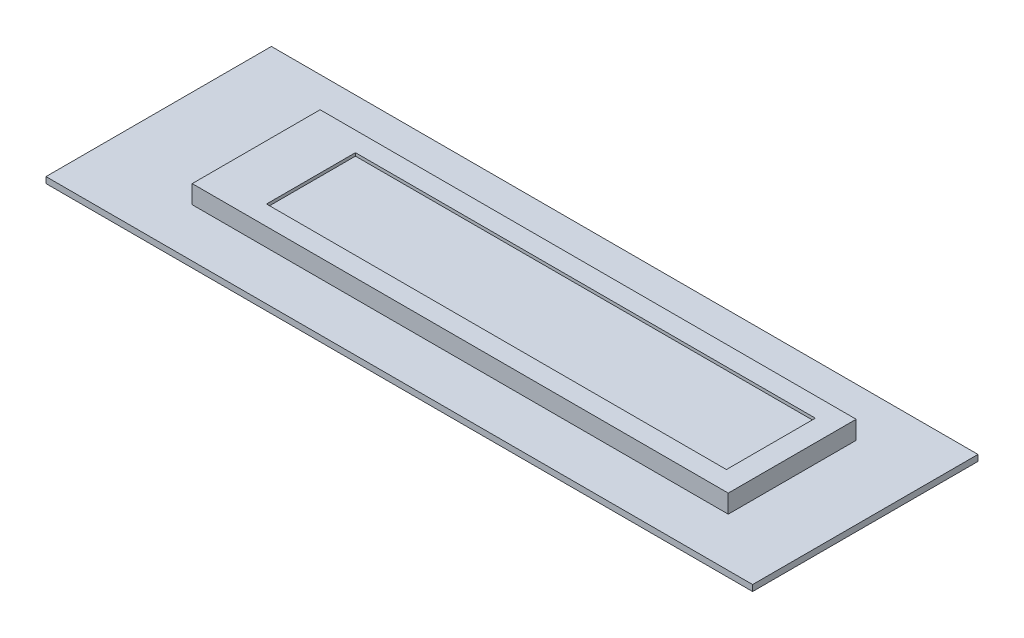
SolidWorks part; units mm, degrees
ref_plane "Front" through (0, 0, 0) normal (0, 0, 1) x (1, 0, 0)
ref_plane "Top" through (0, 0, 0) normal (0, 1, 0) x (1, 0, 0)
ref_plane "Right" through (0, 0, 0) normal (1, 0, 0) x (0, 0, -1)
sketch "Sketch1" plane through (0, 0, 0) normal (0, 1, 0) x (1, 0, 0)
  line L1 (-58, 18.5) -> (58, 18.5)
  line L2 (-58, 18.5) -> (-58, -18.5)
  line L3 (-58, -18.5) -> (58, -18.5)
  line L4 (58, 18.5) -> (58, -18.5)
  line L5 (-58, 18.5) -> (58, -18.5) construction
  line L6 (-58, -18.5) -> (58, 18.5) construction
  point P0 (0, 0)
  dimension "D1" = 37
  dimension "D2" = 116
extrude "Boss-Extrude1" add sketch "Sketch1" along normal blind 1
sketch "Sketch2" plane through (0, 1, 0) normal (0, 1, 0) x (1, 0, 0)
  line L0 (-58, 18.5) -> (-58, -18.5) construction
  line L1 (-42, 10.5) -> (46, 10.5)
  line L2 (-42, 10.5) -> (-42, -10.5)
  line L3 (-42, -10.5) -> (46, -10.5)
  line L4 (46, 10.5) -> (46, -10.5)
  line L5 (-42, 10.5) -> (46, -10.5) construction
  line L6 (-42, -10.5) -> (46, 10.5) construction
  point P0 (2, 0)
  dimension "D1" = 21
  dimension "D2" = 0
  dimension "D3" = 88
  dimension "D4" = 16
extrude "Boss-Extrude2" add sketch "Sketch2" along normal blind 3
sketch "Sketch3" plane through (0, 4, 0) normal (0, 1, 0) x (1, 0, 0)
  line L1 (-33, 7.3) -> (42.5, 7.3)
  line L2 (-33, 7.3) -> (-33, -7.3)
  line L3 (-33, -7.3) -> (42.5, -7.3)
  line L4 (42.5, 7.3) -> (42.5, -7.3)
  line L5 (46, 10.5) -> (-42, 10.5) construction
  line L6 (-42, -10.5) -> (46, -10.5) construction
  line L8 (46, -10.5) -> (46, 10.5) construction
  line L9 (-42, 10.5) -> (-42, -10.5) construction
  point P4 (42.5, 0)
  dimension "D1" = 3.5
  dimension "D2" = 3.2
  dimension "D3" = 3.2
  dimension "D4" = 9
extrude "Cut-Extrude1" cut sketch "Sketch3" against normal blind 0.5
